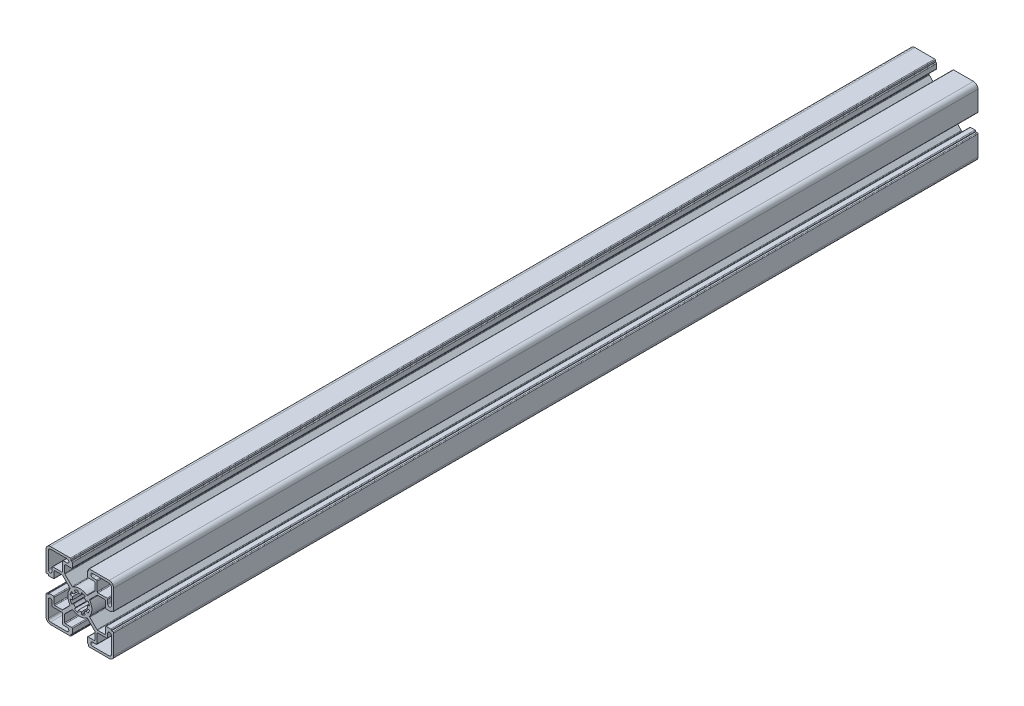
SolidWorks part; units mm, degrees
material "6063-O"
ref_plane "Front Plane" through (0, 0, 0) normal (0, 0, 1) x (1, 0, 0)
ref_plane "Top Plane" through (0, 0, 0) normal (0, 1, 0) x (1, 0, 0)
ref_plane "Right Plane" through (0, 0, 0) normal (1, 0, 0) x (0, 0, -1)
sketch "Sketch1" plane through (0, 0, 0) normal (0, 0, 1) x (1, 0, 0)
  line L0 (0, 22.5) -> (0, -22.5) construction
  line L1 (22.5, 0) -> (-22.5, 0) construction
  line L2 (-5.8, 22.5) -> (5.8, 22.5) construction
  line L3 (-5, 21) -> (5, 21) construction
  line L4 (-10.05, 10.05) -> (10.05, 10.05) construction
  line L5 (0, 0) -> (-10.05, 10.05) construction
  circle A0 centre (0, 0) radius 5 construction
  point P4 (0, 0)
  point P8 (0, 0)
  point P10 (0, 8)
  point P14 (0, 22.5)
  point P17 (0, 21)
  point P19 (0, 10.05)
sketch "Sketch2" plane through (0, 0, 0) normal (1, 0, 0) x (0, 0, -1)
  line L0 (152.4, 0) -> (-152.4, 0) construction
  point P4 (0, 0)
  dimension "D1" = 304.8
sketch "Sketch3" plane through (0, 0, 0) normal (0, 0, 1) x (1, 0, 0)
  line L5 (-21, 8.5375) -> (-21, 19.5)
  line L9 (0, 0) -> (-22.5, 22.5) construction
  line L10 (-11.55, -10.05) -> (-6.3569, -4.8569)
  line L11 (-19.5, 21) -> (-8.5375, 21)
  line L38 (-5.8, 22.5) -> (-5.8, 21)
  line L46 (-5.8, 21) -> (-5, 21)
  line L62 (-5, 21) -> (-5, 17.025)
  line L74 (-5, 17.025) -> (-10.05, 17.025)
  line L76 (-10.05, 17.025) -> (-10.05, 11.55)
  line L77 (-10.05, 11.55) -> (-4.8569, 6.3569)
  line L78 (-18.525, 8.5375) -> (-18.525, 11.55)
  line L79 (-10.05, 17.025) -> (-10.05, 22.5) construction
  line L80 (0, 22.5) -> (0, -22.5) construction
  line L81 (-5.8, 22.5) -> (5.8, 22.5) construction
  line L82 (10.05, 11.55) -> (4.8569, 6.3569)
  line L83 (10.05, 17.025) -> (10.05, 11.55)
  line L84 (5, 17.025) -> (10.05, 17.025)
  line L85 (5, 21) -> (5, 17.025)
  line L86 (5.8, 21) -> (5, 21)
  line L87 (5.8, 22.5) -> (5.8, 21)
  line L88 (-22.5, -5.8) -> (-21, -5.8)
  line L89 (-21, -5.8) -> (-21, -5)
  line L90 (-21, -5) -> (-17.025, -5)
  line L91 (-17.025, -5) -> (-17.025, -10.05)
  line L92 (-17.025, -10.05) -> (-11.55, -10.05)
  line L93 (-11.55, -10.05) -> (-6.3569, -4.8569)
  line L94 (-11.55, 10.05) -> (-6.3569, 4.8569)
  line L95 (-17.025, 10.05) -> (-11.55, 10.05)
  line L96 (-17.025, 5) -> (-17.025, 10.05)
  line L97 (-21, 5) -> (-17.025, 5)
  line L98 (-21, 5.8) -> (-21, 5)
  line L99 (-22.5, 5.8) -> (-21, 5.8)
  line L100 (-22.5, 5.8) -> (-22.5, 19.5)
  line L101 (-19.5, 22.5) -> (-5.8, 22.5)
  line L102 (-18.525, 11.55) -> (-11.55, 11.55)
  line L103 (-8.5375, 18.525) -> (-11.55, 18.525)
  line L104 (-11.55, 18.525) -> (-11.55, 11.55)
  line L108 (5.8, -22.5) -> (5.8, -21)
  line L113 (5.8, -21) -> (5, -21)
  line L117 (5.8, 22.5) -> (19.5, 22.5)
  line L118 (22.5, 19.5) -> (22.5, 5.8)
  line L119 (19.5, -22.5) -> (5.8, -22.5)
  line L120 (0, 0) -> (22.5, 0) construction
  line L121 (-22.5, -19.5) -> (-22.5, -5.8)
  line L136 (5, -21) -> (5, -17.025)
  line L137 (5, -17.025) -> (10.05, -17.025)
  line L138 (10.05, -17.025) -> (10.05, -11.55)
  line L139 (10.05, -11.55) -> (4.8569, -6.3569)
  line L140 (-10.05, -11.55) -> (-4.8569, -6.3569)
  line L141 (-10.05, -17.025) -> (-10.05, -11.55)
  line L142 (-5, -17.025) -> (-10.05, -17.025)
  line L143 (-5, -21) -> (-5, -17.025)
  line L144 (-5.8, -21) -> (-5, -21)
  line L145 (-5.8, -22.5) -> (-5.8, -21)
  line L146 (-5.8, -22.5) -> (-19.5, -22.5)
  line L147 (22.5, 5.8) -> (21, 5.8)
  line L148 (21, 5.8) -> (21, 5)
  line L149 (21, 5) -> (17.025, 5)
  line L150 (17.025, 5) -> (17.025, 10.05)
  line L151 (17.025, 10.05) -> (11.55, 10.05)
  line L152 (11.55, 10.05) -> (6.3569, 4.8569)
  line L153 (11.55, -10.05) -> (6.3569, -4.8569)
  line L154 (17.025, -10.05) -> (11.55, -10.05)
  line L155 (17.025, -5) -> (17.025, -10.05)
  line L156 (21, -5) -> (17.025, -5)
  line L157 (21, -5.8) -> (21, -5)
  line L158 (22.5, -5.8) -> (21, -5.8)
  line L159 (11.55, -10.05) -> (6.3569, -4.8569)
  line L160 (22.5, -5.8) -> (22.5, -19.5)
  line L161 (8.5375, 21) -> (19.5, 21)
  line L162 (21, 19.5) -> (21, 8.5375)
  line L163 (8.5375, 18.525) -> (11.55, 18.525)
  line L164 (11.55, 18.525) -> (11.55, 11.55)
  line L165 (18.525, 8.5375) -> (18.525, 11.55)
  line L166 (18.525, 11.55) -> (11.55, 11.55)
  line L167 (21, -8.5375) -> (21, -19.5)
  line L168 (19.5, -21) -> (8.5375, -21)
  line L169 (18.525, -8.5375) -> (18.525, -11.55)
  line L170 (18.525, -11.55) -> (11.55, -11.55)
  line L171 (8.5375, -18.525) -> (11.55, -18.525)
  line L172 (11.55, -18.525) -> (11.55, -11.55)
  line L173 (-8.5375, -21) -> (-19.5, -21)
  line L174 (-21, -19.5) -> (-21, -8.5375)
  line L175 (-8.5375, -18.525) -> (-11.55, -18.525)
  line L176 (-11.55, -18.525) -> (-11.55, -11.55)
  line L177 (-18.525, -8.5375) -> (-18.525, -11.55)
  line L178 (-18.525, -11.55) -> (-11.55, -11.55)
  line L179 (0, 0) -> (-11.55, 11.55) construction
  line L180 (0, 0) -> (11.55, 11.55) construction
  arc A2 (-21, 19.5) -> (-19.5, 21) centre (-19.5, 19.5) cw
  arc A73 (-4.8569, 6.3569) -> (4.8569, 6.3569) centre (0, 0) cw
  arc A74 (-6.3569, 4.8569) -> (-6.3569, -4.8569) centre (0, 0) ccw
  arc A75 (-19.5, 22.5) -> (-22.5, 19.5) centre (-19.5, 19.5) ccw
  arc A76 (-21, 8.5375) -> (-18.525, 8.5375) centre (-19.7625, 8.5375) ccw
  arc A77 (-8.5375, 21) -> (-8.5375, 18.525) centre (-8.5375, 19.7625) cw
  arc A80 (19.5, 22.5) -> (22.5, 19.5) centre (19.5, 19.5) cw
  arc A81 (22.5, -19.5) -> (19.5, -22.5) centre (19.5, -19.5) cw
  arc A82 (-19.5, -22.5) -> (-22.5, -19.5) centre (-19.5, -19.5) cw
  circle A88 centre (0, 0) radius 5 construction
  circle A89 centre (0, 0) radius 5
  arc A90 (-4.8569, -6.3569) -> (4.8569, -6.3569) centre (0, 0) ccw
  arc A91 (19.5, 21) -> (21, 19.5) centre (19.5, 19.5) cw
  arc A92 (6.3569, 4.8569) -> (6.3569, -4.8569) centre (0, 0) cw
  arc A93 (8.5375, 21) -> (8.5375, 18.525) centre (8.5375, 19.7625) ccw
  arc A94 (21, 8.5375) -> (18.525, 8.5375) centre (19.7625, 8.5375) cw
  arc A95 (21, -19.5) -> (19.5, -21) centre (19.5, -19.5) cw
  arc A96 (21, -8.5375) -> (18.525, -8.5375) centre (19.7625, -8.5375) ccw
  arc A97 (8.5375, -21) -> (8.5375, -18.525) centre (8.5375, -19.7625) cw
  arc A98 (-19.5, -21) -> (-21, -19.5) centre (-19.5, -19.5) cw
  arc A99 (-8.5375, -21) -> (-8.5375, -18.525) centre (-8.5375, -19.7625) ccw
  arc A100 (-21, -8.5375) -> (-18.525, -8.5375) centre (-19.7625, -8.5375) cw
  point P54 (-14.2875, 10.05)
  dimension "D2" = 3
  dimension "D3" = 1.5
  dimension "D4" = 1.5
  dimension "D5" = 1.5
  dimension "D6" = 90
  dimension "D1" = 4
extrude "Boss-Extrude1" add sketch "Sketch3" along normal up to vertex (152.4 mm away) and the other way up to vertex (152.4 mm away) contours A92 L152 L151 L150 L149 L148 L147 L118 A80 L117 L87 L86 L85 L84 L83 L82 A73 L77 L76 L74 L62 L46 L38 L101 A75 L100 L99 L98 L97 L96 L95 L94 A74 L10 L92 L91 L90 L89 L88 L121 A82 L146 L145 L144 L143 L142 L141 L140 A90 L139 L138 up to point (0, 0, 152.4) other way up to point (0, 0, -152.4)
fillet "Fillet1" radius 0.5 58 edges at (5, 21, 0) (5.8, 22.5, 0) (-5.8, 22.5, 0) (-5, 21, 0) (-10.05, 17.025, 0) (-5, 17.025, 0) (5, 17.025, 0) (-22.5, -5.8, 0) (-21, -5, 0) (-17.025, -5, 0) (-17.025, -10.05, 0) (-11.55, -10.05, 0) (-6.3569, -4.8569, 0) (-6.3569, 4.8569, 0) (-11.55, 10.05, 0) (-17.025, 10.05, 0) (-17.025, 5, 0) (-22.5, 5.8, 0) (-21, 5, 0) (-18.525, 11.55, 0) (-11.55, 11.55, 0) (-11.55, 18.525, 0) (4.8569, 6.3569, 0) (-4.8569, 6.3569, 0) (-10.05, 11.55, 0) (10.05, 17.025, 0) (10.05, 11.55, 0) (22.5, -5.8, 0) (21, -5, 0) (17.025, -5, 0) (17.025, -10.05, 0) (6.3569, 4.8569, 0) (11.55, 10.05, 0) (22.5, 5.8, 0) (21, 5, 0) (17.025, 5, 0) (4.8569, -6.3569, 0) (11.55, -11.55, 0) (-11.55, -11.55, 0) (18.525, -11.55, 0) (11.55, -18.525, 0) (10.05, -17.025, 0) (5, -17.025, 0) (5, -21, 0) (5.8, -22.5, 0) (-5.8, -22.5, 0) (-5, -21, 0) (-5, -17.025, 0) (-10.05, -17.025, 0) (-11.55, -18.525, 0) (11.55, 18.525, 0) (18.525, 11.55, 0) (11.55, 11.55, 0) (11.55, -10.05, 0) (6.3569, -4.8569, 0) (-4.8569, -6.3569, 0) (10.05, -11.55, 0) (-10.05, -11.55, 0)
sketch "Sketch4" plane through (0, 0, 152.4) normal (0, 0, 1) x (1, 0, 0)
  line L0 (-1.2681, 6.3751) -> (-0.9755, 4.9039)
  line L1 (0, 0) -> (0, 8) construction
  line L2 (-3.6112, 5.4046) -> (-2.7779, 4.1573)
  line L3 (1.2681, 6.3751) -> (0.9755, 4.9039)
  line L4 (3.6112, 5.4046) -> (2.7779, 4.1573)
  line L5 (5.4046, 3.6112) -> (4.1573, 2.7779)
  line L6 (6.3751, 1.2681) -> (4.9039, 0.9755)
  line L7 (6.3751, -1.2681) -> (4.9039, -0.9755)
  line L8 (5.4046, -3.6112) -> (4.1573, -2.7779)
  line L9 (3.6112, -5.4046) -> (2.7779, -4.1573)
  line L10 (1.2681, -6.3751) -> (0.9755, -4.9039)
  line L11 (-1.2681, -6.3751) -> (-0.9755, -4.9039)
  line L12 (-3.6112, -5.4046) -> (-2.7779, -4.1573)
  line L13 (-5.4046, -3.6112) -> (-4.1573, -2.7779)
  line L14 (-6.3751, -1.2681) -> (-4.9039, -0.9755)
  line L15 (-6.3751, 1.2681) -> (-4.9039, 0.9755)
  line L16 (-5.4046, 3.6112) -> (-4.1573, 2.7779)
  line L17 (0, 0) -> (-0.9755, 4.9039) construction
  line L18 (0, 0) -> (2.7779, 4.1573) construction
  arc A0 (-1.2681, 6.3751) -> (-3.6112, 5.4046) centre (0, 0) ccw
  circle A1 centre (0, 0) radius 5 construction
  arc A2 (-0.9755, 4.9039) -> (-2.7779, 4.1573) centre (0, 0) ccw
  arc A4 (2.7779, 4.1573) -> (0.9755, 4.9039) centre (0, 0) ccw
  arc A5 (3.6112, 5.4046) -> (1.2681, 6.3751) centre (0, 0) ccw
  arc A6 (4.9039, 0.9755) -> (4.1573, 2.7779) centre (0, 0) ccw
  arc A7 (6.3751, 1.2681) -> (5.4046, 3.6112) centre (0, 0) ccw
  arc A8 (4.1573, -2.7779) -> (4.9039, -0.9755) centre (0, 0) ccw
  arc A9 (5.4046, -3.6112) -> (6.3751, -1.2681) centre (0, 0) ccw
  arc A10 (0.9755, -4.9039) -> (2.7779, -4.1573) centre (0, 0) ccw
  arc A11 (1.2681, -6.3751) -> (3.6112, -5.4046) centre (0, 0) ccw
  arc A12 (-2.7779, -4.1573) -> (-0.9755, -4.9039) centre (0, 0) ccw
  arc A13 (-3.6112, -5.4046) -> (-1.2681, -6.3751) centre (0, 0) ccw
  arc A14 (-4.9039, -0.9755) -> (-4.1573, -2.7779) centre (0, 0) ccw
  arc A15 (-6.3751, -1.2681) -> (-5.4046, -3.6112) centre (0, 0) ccw
  arc A16 (-4.1573, 2.7779) -> (-4.9039, 0.9755) centre (0, 0) ccw
  arc A17 (-5.4046, 3.6112) -> (-6.3751, 1.2681) centre (0, 0) ccw
  dimension "D1" = 1.5
  dimension "D2" = 22.5
  dimension "D5" = 45
  dimension "D4" = 8
extrude "Cut-Extrude1" cut sketch "Sketch4" against normal through all
sketch "Sketch5" plane through (0, 0, 152.4) normal (0, 0, 1) x (1, 0, 0)
  line L6 (-11.55, -18.025) -> (-11.55, -12.05)
  line L7 (-8.5375, -18.525) -> (-11.05, -18.525)
  line L8 (-19.5, -21) -> (-8.5375, -21)
  line L9 (-21, -8.5375) -> (-21, -19.5)
  line L10 (-18.525, -11.55) -> (-18.525, -8.5375)
  line L11 (-12.05, -11.55) -> (-18.525, -11.55)
  line L12 (-11.55, -18.025) -> (-11.55, -12.05)
  line L13 (-8.5375, -18.525) -> (-11.05, -18.525)
  line L14 (-19.5, -21) -> (-8.5375, -21)
  line L15 (-21, -8.5375) -> (-21, -19.5)
  line L16 (-0.9755, 4.9039) -> (-1.2681, 6.3751)
  line L17 (1.2681, 6.3751) -> (0.9755, 4.9039)
  line L18 (2.7779, 4.1573) -> (3.6112, 5.4046)
  line L19 (5.4046, 3.6112) -> (4.1573, 2.7779)
  line L20 (4.9039, 0.9755) -> (6.3751, 1.2681)
  line L21 (6.3751, -1.2681) -> (4.9039, -0.9755)
  line L22 (4.1573, -2.7779) -> (5.4046, -3.6112)
  line L23 (3.6112, -5.4046) -> (2.7779, -4.1573)
  line L24 (0.9755, -4.9039) -> (1.2681, -6.3751)
  line L25 (-1.2681, -6.3751) -> (-0.9755, -4.9039)
  line L26 (-2.7779, -4.1573) -> (-3.6112, -5.4046)
  line L27 (-5.4046, -3.6112) -> (-4.1573, -2.7779)
  line L28 (-4.9039, -0.9755) -> (-6.3751, -1.2681)
  line L29 (-6.3751, 1.2681) -> (-4.9039, 0.9755)
  line L30 (-4.1573, 2.7779) -> (-5.4046, 3.6112)
  line L31 (-3.6112, 5.4046) -> (-2.7779, 4.1573)
  line L32 (-0.9755, 4.9039) -> (-1.2681, 6.3751)
  line L33 (1.2681, 6.3751) -> (0.9755, 4.9039)
  line L34 (2.7779, 4.1573) -> (3.6112, 5.4046)
  line L35 (5.4046, 3.6112) -> (4.1573, 2.7779)
  line L36 (4.9039, 0.9755) -> (6.3751, 1.2681)
  line L37 (6.3751, -1.2681) -> (4.9039, -0.9755)
  line L38 (4.1573, -2.7779) -> (5.4046, -3.6112)
  line L39 (3.6112, -5.4046) -> (2.7779, -4.1573)
  line L40 (0.9755, -4.9039) -> (1.2681, -6.3751)
  line L41 (-1.2681, -6.3751) -> (-0.9755, -4.9039)
  line L42 (-2.7779, -4.1573) -> (-3.6112, -5.4046)
  line L43 (-5.4046, -3.6112) -> (-4.1573, -2.7779)
  line L44 (-4.9039, -0.9755) -> (-6.3751, -1.2681)
  line L45 (-6.3751, 1.2681) -> (-4.9039, 0.9755)
  line L46 (-4.1573, 2.7779) -> (-5.4046, 3.6112)
  line L47 (-3.6112, 5.4046) -> (-2.7779, 4.1573)
  line L48 (-18.525, -11.55) -> (-18.525, -8.5375)
  line L49 (-12.05, -11.55) -> (-18.525, -11.55)
  line L50 (18.025, -11.55) -> (12.05, -11.55)
  line L51 (18.525, -8.5375) -> (18.525, -11.05)
  line L52 (21, -19.5) -> (21, -8.5375)
  line L53 (8.5375, -21) -> (19.5, -21)
  line L54 (11.05, -18.525) -> (8.5375, -18.525)
  line L55 (11.55, -12.05) -> (11.55, -18.025)
  line L56 (22.5, -19.5) -> (22.5, -6.3)
  line L57 (22, -5.8) -> (21, -5.8)
  line L58 (21, -5.8) -> (21, -5.5)
  line L59 (20.5, -5) -> (17.525, -5)
  line L60 (17.025, -5.5) -> (17.025, -9.55)
  line L61 (16.525, -10.05) -> (11.7571, -10.05)
  line L62 (11.4036, -9.9036) -> (6.6582, -5.1582)
  line L63 (6.6582, 5.1582) -> (11.4036, 9.9036)
  line L64 (11.7571, 10.05) -> (17.025, 10.05)
  line L65 (17.025, 10.05) -> (17.025, 5.5)
  line L66 (17.525, 5) -> (20.5, 5)
  line L67 (21, 5.5) -> (21, 5.8)
  line L68 (21, 5.8) -> (22, 5.8)
  line L69 (22.5, 6.3) -> (22.5, 19.5)
  line L70 (19.5, 22.5) -> (6.3, 22.5)
  line L71 (5.8, 22) -> (5.8, 21)
  line L72 (5.8, 21) -> (5.5, 21)
  line L73 (5, 20.5) -> (5, 17.525)
  line L74 (5.5, 17.025) -> (9.55, 17.025)
  line L75 (10.05, 16.525) -> (10.05, 11.7571)
  line L76 (9.9036, 11.4036) -> (5.1582, 6.6582)
  line L77 (-5.1582, 6.6582) -> (-9.9036, 11.4036)
  line L78 (-10.05, 11.7571) -> (-10.05, 16.525)
  line L79 (-9.55, 17.025) -> (-5.5, 17.025)
  line L80 (-5, 17.525) -> (-5, 20.5)
  line L81 (-5.5, 21) -> (-5.8, 21)
  line L82 (-5.8, 21) -> (-5.8, 22)
  line L83 (-6.3, 22.5) -> (-19.5, 22.5)
  line L84 (-22.5, 19.5) -> (-22.5, 6.3)
  line L85 (-22, 5.8) -> (-21, 5.8)
  line L86 (-21, 5.8) -> (-21, 5.5)
  line L87 (-20.5, 5) -> (-17.525, 5)
  line L88 (-17.025, 5.5) -> (-17.025, 9.55)
  line L89 (-16.525, 10.05) -> (-11.7571, 10.05)
  line L90 (-11.4036, 9.9036) -> (-6.6582, 5.1582)
  line L91 (-6.6582, -5.1582) -> (-11.4036, -9.9036)
  line L92 (-11.7571, -10.05) -> (-16.525, -10.05)
  line L93 (-17.025, -9.55) -> (-17.025, -5.5)
  line L94 (-17.525, -5) -> (-20.5, -5)
  line L95 (-21, -5.5) -> (-21, -5.8)
  line L96 (-21, -5.8) -> (-22, -5.8)
  line L97 (-22.5, -6.3) -> (-22.5, -19.5)
  line L98 (-19.5, -22.5) -> (-6.3, -22.5)
  line L99 (-5.8, -22) -> (-5.8, -21)
  line L100 (-5.8, -21) -> (-5.5, -21)
  line L101 (-5, -20.5) -> (-5, -17.525)
  line L102 (-5.5, -17.025) -> (-9.55, -17.025)
  line L103 (-10.05, -16.525) -> (-10.05, -11.7571)
  line L104 (-9.9036, -11.4036) -> (-5.1582, -6.6582)
  line L105 (5.1582, -6.6582) -> (9.9036, -11.4036)
  line L106 (10.05, -11.7571) -> (10.05, -16.525)
  line L107 (9.55, -17.025) -> (5.5, -17.025)
  line L108 (5, -17.525) -> (5, -20.5)
  line L109 (5.5, -21) -> (5.8, -21)
  line L110 (5.8, -21) -> (5.8, -22)
  line L111 (6.3, -22.5) -> (19.5, -22.5)
  line L112 (22.5, -19.5) -> (22.5, -6.3)
  line L113 (22, -5.8) -> (21, -5.8)
  line L114 (21, -5.8) -> (21, -5.5)
  line L115 (20.5, -5) -> (17.525, -5)
  line L116 (17.025, -5.5) -> (17.025, -9.55)
  line L117 (16.525, -10.05) -> (11.7571, -10.05)
  line L118 (11.4036, -9.9036) -> (6.6582, -5.1582)
  line L119 (6.6582, 5.1582) -> (11.4036, 9.9036)
  line L120 (11.7571, 10.05) -> (17.025, 10.05)
  line L121 (17.025, 10.05) -> (17.025, 5.5)
  line L122 (17.525, 5) -> (20.5, 5)
  line L123 (21, 5.5) -> (21, 5.8)
  line L124 (21, 5.8) -> (22, 5.8)
  line L125 (22.5, 6.3) -> (22.5, 19.5)
  line L126 (19.5, 22.5) -> (6.3, 22.5)
  line L127 (5.8, 22) -> (5.8, 21)
  line L128 (5.8, 21) -> (5.5, 21)
  line L129 (5, 20.5) -> (5, 17.525)
  line L130 (5.5, 17.025) -> (9.55, 17.025)
  line L131 (10.05, 16.525) -> (10.05, 11.7571)
  line L132 (9.9036, 11.4036) -> (5.1582, 6.6582)
  line L133 (-5.1582, 6.6582) -> (-9.9036, 11.4036)
  line L134 (-10.05, 11.7571) -> (-10.05, 16.525)
  line L135 (-9.55, 17.025) -> (-5.5, 17.025)
  line L136 (-5, 17.525) -> (-5, 20.5)
  line L137 (-5.5, 21) -> (-5.8, 21)
  line L138 (-5.8, 21) -> (-5.8, 22)
  line L139 (-6.3, 22.5) -> (-19.5, 22.5)
  line L140 (-22.5, 19.5) -> (-22.5, 6.3)
  line L141 (-22, 5.8) -> (-21, 5.8)
  line L142 (-21, 5.8) -> (-21, 5.5)
  line L143 (-20.5, 5) -> (-17.525, 5)
  line L144 (-17.025, 5.5) -> (-17.025, 9.55)
  line L145 (-16.525, 10.05) -> (-11.7571, 10.05)
  line L146 (-11.4036, 9.9036) -> (-6.6582, 5.1582)
  line L147 (-6.6582, -5.1582) -> (-11.4036, -9.9036)
  line L148 (-11.7571, -10.05) -> (-16.525, -10.05)
  line L149 (-17.025, -9.55) -> (-17.025, -5.5)
  line L150 (-17.525, -5) -> (-20.5, -5)
  line L151 (-21, -5.5) -> (-21, -5.8)
  line L152 (-21, -5.8) -> (-22, -5.8)
  line L153 (-22.5, -6.3) -> (-22.5, -19.5)
  line L154 (-19.5, -22.5) -> (-6.3, -22.5)
  line L155 (-5.8, -22) -> (-5.8, -21)
  line L156 (-5.8, -21) -> (-5.5, -21)
  line L157 (-5, -20.5) -> (-5, -17.525)
  line L158 (-5.5, -17.025) -> (-9.55, -17.025)
  line L159 (-10.05, -16.525) -> (-10.05, -11.7571)
  line L160 (-9.9036, -11.4036) -> (-5.1582, -6.6582)
  line L161 (5.1582, -6.6582) -> (9.9036, -11.4036)
  line L162 (10.05, -11.7571) -> (10.05, -16.525)
  line L163 (9.55, -17.025) -> (5.5, -17.025)
  line L164 (5, -17.525) -> (5, -20.5)
  line L165 (5.5, -21) -> (5.8, -21)
  line L166 (5.8, -21) -> (5.8, -22)
  line L167 (6.3, -22.5) -> (19.5, -22.5)
  line L168 (18.025, -11.55) -> (12.05, -11.55)
  line L169 (18.525, -8.5375) -> (18.525, -11.05)
  line L170 (21, -19.5) -> (21, -8.5375)
  line L171 (8.5375, -21) -> (19.5, -21)
  line L172 (11.05, -18.525) -> (8.5375, -18.525)
  line L173 (11.55, -12.05) -> (11.55, -18.025)
  line L174 (11.55, 18.025) -> (11.55, 12.05)
  line L175 (8.5375, 18.525) -> (11.05, 18.525)
  line L176 (19.5, 21) -> (8.5375, 21)
  line L177 (21, 8.5375) -> (21, 19.5)
  line L178 (18.525, 11.05) -> (18.525, 8.5375)
  line L179 (12.05, 11.55) -> (18.025, 11.55)
  line L180 (11.55, 18.025) -> (11.55, 12.05)
  line L181 (8.5375, 18.525) -> (11.05, 18.525)
  line L182 (19.5, 21) -> (8.5375, 21)
  line L183 (21, 8.5375) -> (21, 19.5)
  line L184 (18.525, 11.05) -> (18.525, 8.5375)
  line L185 (12.05, 11.55) -> (18.025, 11.55)
  line L186 (-18.025, 11.55) -> (-12.05, 11.55)
  line L187 (-18.525, 8.5375) -> (-18.525, 11.05)
  line L188 (-21, 19.5) -> (-21, 8.5375)
  line L189 (-8.5375, 21) -> (-19.5, 21)
  line L190 (-11.05, 18.525) -> (-8.5375, 18.525)
  line L191 (-11.55, 12.05) -> (-11.55, 18.025)
  line L192 (-18.025, 11.55) -> (-12.05, 11.55)
  line L193 (-18.525, 8.5375) -> (-18.525, 11.05)
  line L194 (-21, 19.5) -> (-21, 8.5375)
  line L195 (-8.5375, 21) -> (-19.5, 21)
  line L196 (-11.05, 18.525) -> (-8.5375, 18.525)
  line L197 (-11.55, 12.05) -> (-11.55, 18.025)
  arc A5 (-11.55, -18.025) -> (-11.05, -18.525) centre (-11.05, -18.025) ccw
  arc A6 (-8.5375, -21) -> (-8.5375, -18.525) centre (-8.5375, -19.7625) ccw
  arc A7 (-21, -19.5) -> (-19.5, -21) centre (-19.5, -19.5) ccw
  arc A8 (-18.525, -8.5375) -> (-21, -8.5375) centre (-19.7625, -8.5375) ccw
  arc A9 (-11.55, -12.05) -> (-12.05, -11.55) centre (-12.05, -12.05) ccw
  arc A10 (-11.55, -18.025) -> (-11.05, -18.525) centre (-11.05, -18.025) ccw
  arc A11 (-8.5375, -21) -> (-8.5375, -18.525) centre (-8.5375, -19.7625) ccw
  arc A12 (-21, -19.5) -> (-19.5, -21) centre (-19.5, -19.5) ccw
  arc A13 (-18.525, -8.5375) -> (-21, -8.5375) centre (-19.7625, -8.5375) ccw
  arc A14 (-11.55, -12.05) -> (-12.05, -11.55) centre (-12.05, -12.05) ccw
  arc A16 (0.9755, 4.9039) -> (-0.9755, 4.9039) centre (0, 0) ccw
  arc A17 (3.6112, 5.4046) -> (1.2681, 6.3751) centre (0, 0) ccw
  arc A18 (4.1573, 2.7779) -> (2.7779, 4.1573) centre (0, 0) ccw
  arc A19 (6.3751, 1.2681) -> (5.4046, 3.6112) centre (0, 0) ccw
  arc A20 (4.9039, -0.9755) -> (4.9039, 0.9755) centre (0, 0) ccw
  arc A21 (5.4046, -3.6112) -> (6.3751, -1.2681) centre (0, 0) ccw
  arc A22 (2.7779, -4.1573) -> (4.1573, -2.7779) centre (0, 0) ccw
  arc A23 (1.2681, -6.3751) -> (3.6112, -5.4046) centre (0, 0) ccw
  arc A24 (-0.9755, -4.9039) -> (0.9755, -4.9039) centre (0, 0) ccw
  arc A25 (-3.6112, -5.4046) -> (-1.2681, -6.3751) centre (0, 0) ccw
  arc A26 (-4.1573, -2.7779) -> (-2.7779, -4.1573) centre (0, 0) ccw
  arc A27 (-6.3751, -1.2681) -> (-5.4046, -3.6112) centre (0, 0) ccw
  arc A28 (-4.9039, 0.9755) -> (-4.9039, -0.9755) centre (0, 0) ccw
  arc A29 (-5.4046, 3.6112) -> (-6.3751, 1.2681) centre (0, 0) ccw
  arc A30 (-2.7779, 4.1573) -> (-4.1573, 2.7779) centre (0, 0) ccw
  arc A31 (-1.2681, 6.3751) -> (-3.6112, 5.4046) centre (0, 0) ccw
  arc A32 (0.9755, 4.9039) -> (-0.9755, 4.9039) centre (0, 0) ccw
  arc A33 (3.6112, 5.4046) -> (1.2681, 6.3751) centre (0, 0) ccw
  arc A34 (4.1573, 2.7779) -> (2.7779, 4.1573) centre (0, 0) ccw
  arc A35 (6.3751, 1.2681) -> (5.4046, 3.6112) centre (0, 0) ccw
  arc A36 (4.9039, -0.9755) -> (4.9039, 0.9755) centre (0, 0) ccw
  arc A37 (5.4046, -3.6112) -> (6.3751, -1.2681) centre (0, 0) ccw
  arc A38 (2.7779, -4.1573) -> (4.1573, -2.7779) centre (0, 0) ccw
  arc A39 (1.2681, -6.3751) -> (3.6112, -5.4046) centre (0, 0) ccw
  arc A40 (-0.9755, -4.9039) -> (0.9755, -4.9039) centre (0, 0) ccw
  arc A41 (-3.6112, -5.4046) -> (-1.2681, -6.3751) centre (0, 0) ccw
  arc A42 (-4.1573, -2.7779) -> (-2.7779, -4.1573) centre (0, 0) ccw
  arc A43 (-6.3751, -1.2681) -> (-5.4046, -3.6112) centre (0, 0) ccw
  arc A44 (-4.9039, 0.9755) -> (-4.9039, -0.9755) centre (0, 0) ccw
  arc A45 (-5.4046, 3.6112) -> (-6.3751, 1.2681) centre (0, 0) ccw
  arc A46 (-2.7779, 4.1573) -> (-4.1573, 2.7779) centre (0, 0) ccw
  arc A47 (-1.2681, 6.3751) -> (-3.6112, 5.4046) centre (0, 0) ccw
  arc A48 (18.025, -11.55) -> (18.525, -11.05) centre (18.025, -11.05) ccw
  arc A49 (21, -8.5375) -> (18.525, -8.5375) centre (19.7625, -8.5375) ccw
  arc A50 (19.5, -21) -> (21, -19.5) centre (19.5, -19.5) ccw
  arc A51 (8.5375, -18.525) -> (8.5375, -21) centre (8.5375, -19.7625) ccw
  arc A52 (11.05, -18.525) -> (11.55, -18.025) centre (11.05, -18.025) ccw
  arc A53 (12.05, -11.55) -> (11.55, -12.05) centre (12.05, -12.05) ccw
  arc A54 (18.025, -11.55) -> (18.525, -11.05) centre (18.025, -11.05) ccw
  arc A55 (22.5, -6.3) -> (22, -5.8) centre (22, -6.3) ccw
  arc A56 (21, -5.5) -> (20.5, -5) centre (20.5, -5.5) ccw
  arc A57 (17.525, -5) -> (17.025, -5.5) centre (17.525, -5.5) ccw
  arc A58 (16.525, -10.05) -> (17.025, -9.55) centre (16.525, -9.55) ccw
  arc A59 (11.4036, -9.9036) -> (11.7571, -10.05) centre (11.7571, -9.55) ccw
  arc A60 (6.5993, -4.522) -> (6.6582, -5.1582) centre (7.0118, -4.8047) ccw
  arc A61 (6.5993, -4.522) -> (6.5993, 4.522) centre (0, 0) ccw
  arc A62 (6.6582, 5.1582) -> (6.5993, 4.522) centre (7.0118, 4.8047) ccw
  arc A63 (11.7571, 10.05) -> (11.4036, 9.9036) centre (11.7571, 9.55) ccw
  arc A64 (17.025, 5.5) -> (17.525, 5) centre (17.525, 5.5) ccw
  arc A65 (20.5, 5) -> (21, 5.5) centre (20.5, 5.5) ccw
  arc A66 (22, 5.8) -> (22.5, 6.3) centre (22, 6.3) ccw
  arc A67 (22.5, 19.5) -> (19.5, 22.5) centre (19.5, 19.5) ccw
  arc A68 (6.3, 22.5) -> (5.8, 22) centre (6.3, 22) ccw
  arc A69 (5.5, 21) -> (5, 20.5) centre (5.5, 20.5) ccw
  arc A70 (5, 17.525) -> (5.5, 17.025) centre (5.5, 17.525) ccw
  arc A71 (10.05, 16.525) -> (9.55, 17.025) centre (9.55, 16.525) ccw
  arc A72 (9.9036, 11.4036) -> (10.05, 11.7571) centre (9.55, 11.7571) ccw
  arc A73 (4.522, 6.5993) -> (5.1582, 6.6582) centre (4.8047, 7.0118) ccw
  arc A74 (4.522, 6.5993) -> (-4.522, 6.5993) centre (0, 0) ccw
  arc A75 (-5.1582, 6.6582) -> (-4.522, 6.5993) centre (-4.8047, 7.0118) ccw
  arc A76 (-10.05, 11.7571) -> (-9.9036, 11.4036) centre (-9.55, 11.7571) ccw
  arc A77 (-9.55, 17.025) -> (-10.05, 16.525) centre (-9.55, 16.525) ccw
  arc A78 (-5.5, 17.025) -> (-5, 17.525) centre (-5.5, 17.525) ccw
  arc A79 (-5, 20.5) -> (-5.5, 21) centre (-5.5, 20.5) ccw
  arc A80 (-5.8, 22) -> (-6.3, 22.5) centre (-6.3, 22) ccw
  arc A81 (-19.5, 22.5) -> (-22.5, 19.5) centre (-19.5, 19.5) ccw
  arc A82 (-22.5, 6.3) -> (-22, 5.8) centre (-22, 6.3) ccw
  arc A83 (-21, 5.5) -> (-20.5, 5) centre (-20.5, 5.5) ccw
  arc A84 (-17.525, 5) -> (-17.025, 5.5) centre (-17.525, 5.5) ccw
  arc A85 (-16.525, 10.05) -> (-17.025, 9.55) centre (-16.525, 9.55) ccw
  arc A86 (-11.4036, 9.9036) -> (-11.7571, 10.05) centre (-11.7571, 9.55) ccw
  arc A87 (-6.5993, 4.522) -> (-6.6582, 5.1582) centre (-7.0118, 4.8047) ccw
  arc A88 (-6.5993, 4.522) -> (-6.5993, -4.522) centre (0, 0) ccw
  arc A89 (-6.6582, -5.1582) -> (-6.5993, -4.522) centre (-7.0118, -4.8047) ccw
  arc A90 (-11.7571, -10.05) -> (-11.4036, -9.9036) centre (-11.7571, -9.55) ccw
  arc A91 (-17.025, -9.55) -> (-16.525, -10.05) centre (-16.525, -9.55) ccw
  arc A92 (-17.025, -5.5) -> (-17.525, -5) centre (-17.525, -5.5) ccw
  arc A93 (-20.5, -5) -> (-21, -5.5) centre (-20.5, -5.5) ccw
  arc A94 (-22, -5.8) -> (-22.5, -6.3) centre (-22, -6.3) ccw
  arc A95 (-22.5, -19.5) -> (-19.5, -22.5) centre (-19.5, -19.5) ccw
  arc A96 (-6.3, -22.5) -> (-5.8, -22) centre (-6.3, -22) ccw
  arc A97 (-5.5, -21) -> (-5, -20.5) centre (-5.5, -20.5) ccw
  arc A98 (-5, -17.525) -> (-5.5, -17.025) centre (-5.5, -17.525) ccw
  arc A99 (-10.05, -16.525) -> (-9.55, -17.025) centre (-9.55, -16.525) ccw
  arc A100 (-9.9036, -11.4036) -> (-10.05, -11.7571) centre (-9.55, -11.7571) ccw
  arc A101 (-4.522, -6.5993) -> (-5.1582, -6.6582) centre (-4.8047, -7.0118) ccw
  arc A102 (-4.522, -6.5993) -> (4.522, -6.5993) centre (0, 0) ccw
  arc A103 (5.1582, -6.6582) -> (4.522, -6.5993) centre (4.8047, -7.0118) ccw
  arc A104 (10.05, -11.7571) -> (9.9036, -11.4036) centre (9.55, -11.7571) ccw
  arc A105 (9.55, -17.025) -> (10.05, -16.525) centre (9.55, -16.525) ccw
  arc A106 (5.5, -17.025) -> (5, -17.525) centre (5.5, -17.525) ccw
  arc A107 (5, -20.5) -> (5.5, -21) centre (5.5, -20.5) ccw
  arc A108 (5.8, -22) -> (6.3, -22.5) centre (6.3, -22) ccw
  arc A109 (19.5, -22.5) -> (22.5, -19.5) centre (19.5, -19.5) ccw
  arc A110 (22.5, -6.3) -> (22, -5.8) centre (22, -6.3) ccw
  arc A111 (21, -5.5) -> (20.5, -5) centre (20.5, -5.5) ccw
  arc A112 (17.525, -5) -> (17.025, -5.5) centre (17.525, -5.5) ccw
  arc A113 (16.525, -10.05) -> (17.025, -9.55) centre (16.525, -9.55) ccw
  arc A114 (11.4036, -9.9036) -> (11.7571, -10.05) centre (11.7571, -9.55) ccw
  arc A115 (6.5993, -4.522) -> (6.6582, -5.1582) centre (7.0118, -4.8047) ccw
  arc A116 (6.5993, -4.522) -> (6.5993, 4.522) centre (0, 0) ccw
  arc A117 (6.6582, 5.1582) -> (6.5993, 4.522) centre (7.0118, 4.8047) ccw
  arc A118 (11.7571, 10.05) -> (11.4036, 9.9036) centre (11.7571, 9.55) ccw
  arc A119 (17.025, 5.5) -> (17.525, 5) centre (17.525, 5.5) ccw
  arc A120 (20.5, 5) -> (21, 5.5) centre (20.5, 5.5) ccw
  arc A121 (22, 5.8) -> (22.5, 6.3) centre (22, 6.3) ccw
  arc A122 (22.5, 19.5) -> (19.5, 22.5) centre (19.5, 19.5) ccw
  arc A123 (6.3, 22.5) -> (5.8, 22) centre (6.3, 22) ccw
  arc A124 (5.5, 21) -> (5, 20.5) centre (5.5, 20.5) ccw
  arc A125 (5, 17.525) -> (5.5, 17.025) centre (5.5, 17.525) ccw
  arc A126 (10.05, 16.525) -> (9.55, 17.025) centre (9.55, 16.525) ccw
  arc A127 (9.9036, 11.4036) -> (10.05, 11.7571) centre (9.55, 11.7571) ccw
  arc A128 (4.522, 6.5993) -> (5.1582, 6.6582) centre (4.8047, 7.0118) ccw
  arc A129 (4.522, 6.5993) -> (-4.522, 6.5993) centre (0, 0) ccw
  arc A130 (-5.1582, 6.6582) -> (-4.522, 6.5993) centre (-4.8047, 7.0118) ccw
  arc A131 (-10.05, 11.7571) -> (-9.9036, 11.4036) centre (-9.55, 11.7571) ccw
  arc A132 (-9.55, 17.025) -> (-10.05, 16.525) centre (-9.55, 16.525) ccw
  arc A133 (-5.5, 17.025) -> (-5, 17.525) centre (-5.5, 17.525) ccw
  arc A134 (-5, 20.5) -> (-5.5, 21) centre (-5.5, 20.5) ccw
  arc A135 (-5.8, 22) -> (-6.3, 22.5) centre (-6.3, 22) ccw
  arc A136 (-19.5, 22.5) -> (-22.5, 19.5) centre (-19.5, 19.5) ccw
  arc A137 (-22.5, 6.3) -> (-22, 5.8) centre (-22, 6.3) ccw
  arc A138 (-21, 5.5) -> (-20.5, 5) centre (-20.5, 5.5) ccw
  arc A139 (-17.525, 5) -> (-17.025, 5.5) centre (-17.525, 5.5) ccw
  arc A140 (-16.525, 10.05) -> (-17.025, 9.55) centre (-16.525, 9.55) ccw
  arc A141 (-11.4036, 9.9036) -> (-11.7571, 10.05) centre (-11.7571, 9.55) ccw
  arc A142 (-6.5993, 4.522) -> (-6.6582, 5.1582) centre (-7.0118, 4.8047) ccw
  arc A143 (-6.5993, 4.522) -> (-6.5993, -4.522) centre (0, 0) ccw
  arc A144 (-6.6582, -5.1582) -> (-6.5993, -4.522) centre (-7.0118, -4.8047) ccw
  arc A145 (-11.7571, -10.05) -> (-11.4036, -9.9036) centre (-11.7571, -9.55) ccw
  arc A146 (-17.025, -9.55) -> (-16.525, -10.05) centre (-16.525, -9.55) ccw
  arc A147 (-17.025, -5.5) -> (-17.525, -5) centre (-17.525, -5.5) ccw
  arc A148 (-20.5, -5) -> (-21, -5.5) centre (-20.5, -5.5) ccw
  arc A149 (-22, -5.8) -> (-22.5, -6.3) centre (-22, -6.3) ccw
  arc A150 (-22.5, -19.5) -> (-19.5, -22.5) centre (-19.5, -19.5) ccw
  arc A151 (-6.3, -22.5) -> (-5.8, -22) centre (-6.3, -22) ccw
  arc A152 (-5.5, -21) -> (-5, -20.5) centre (-5.5, -20.5) ccw
  arc A153 (-5, -17.525) -> (-5.5, -17.025) centre (-5.5, -17.525) ccw
  arc A154 (-10.05, -16.525) -> (-9.55, -17.025) centre (-9.55, -16.525) ccw
  arc A155 (-9.9036, -11.4036) -> (-10.05, -11.7571) centre (-9.55, -11.7571) ccw
  arc A156 (-4.522, -6.5993) -> (-5.1582, -6.6582) centre (-4.8047, -7.0118) ccw
  arc A157 (-4.522, -6.5993) -> (4.522, -6.5993) centre (0, 0) ccw
  arc A158 (5.1582, -6.6582) -> (4.522, -6.5993) centre (4.8047, -7.0118) ccw
  arc A159 (10.05, -11.7571) -> (9.9036, -11.4036) centre (9.55, -11.7571) ccw
  arc A160 (9.55, -17.025) -> (10.05, -16.525) centre (9.55, -16.525) ccw
  arc A161 (5.5, -17.025) -> (5, -17.525) centre (5.5, -17.525) ccw
  arc A162 (5, -20.5) -> (5.5, -21) centre (5.5, -20.5) ccw
  arc A163 (5.8, -22) -> (6.3, -22.5) centre (6.3, -22) ccw
  arc A164 (19.5, -22.5) -> (22.5, -19.5) centre (19.5, -19.5) ccw
  arc A165 (21, -8.5375) -> (18.525, -8.5375) centre (19.7625, -8.5375) ccw
  arc A166 (19.5, -21) -> (21, -19.5) centre (19.5, -19.5) ccw
  arc A167 (8.5375, -18.525) -> (8.5375, -21) centre (8.5375, -19.7625) ccw
  arc A168 (11.05, -18.525) -> (11.55, -18.025) centre (11.05, -18.025) ccw
  arc A169 (12.05, -11.55) -> (11.55, -12.05) centre (12.05, -12.05) ccw
  arc A170 (11.55, 18.025) -> (11.05, 18.525) centre (11.05, 18.025) ccw
  arc A171 (8.5375, 21) -> (8.5375, 18.525) centre (8.5375, 19.7625) ccw
  arc A172 (21, 19.5) -> (19.5, 21) centre (19.5, 19.5) ccw
  arc A173 (18.525, 8.5375) -> (21, 8.5375) centre (19.7625, 8.5375) ccw
  arc A174 (18.525, 11.05) -> (18.025, 11.55) centre (18.025, 11.05) ccw
  arc A175 (11.55, 12.05) -> (12.05, 11.55) centre (12.05, 12.05) ccw
  arc A176 (11.55, 18.025) -> (11.05, 18.525) centre (11.05, 18.025) ccw
  arc A177 (8.5375, 21) -> (8.5375, 18.525) centre (8.5375, 19.7625) ccw
  arc A178 (21, 19.5) -> (19.5, 21) centre (19.5, 19.5) ccw
  arc A179 (18.525, 8.5375) -> (21, 8.5375) centre (19.7625, 8.5375) ccw
  arc A180 (18.525, 11.05) -> (18.025, 11.55) centre (18.025, 11.05) ccw
  arc A181 (11.55, 12.05) -> (12.05, 11.55) centre (12.05, 12.05) ccw
  arc A182 (-18.025, 11.55) -> (-18.525, 11.05) centre (-18.025, 11.05) ccw
  arc A183 (-21, 8.5375) -> (-18.525, 8.5375) centre (-19.7625, 8.5375) ccw
  arc A184 (-19.5, 21) -> (-21, 19.5) centre (-19.5, 19.5) ccw
  arc A185 (-8.5375, 18.525) -> (-8.5375, 21) centre (-8.5375, 19.7625) ccw
  arc A186 (-11.05, 18.525) -> (-11.55, 18.025) centre (-11.05, 18.025) ccw
  arc A187 (-12.05, 11.55) -> (-11.55, 12.05) centre (-12.05, 12.05) ccw
  arc A188 (-18.025, 11.55) -> (-18.525, 11.05) centre (-18.025, 11.05) ccw
  arc A189 (-21, 8.5375) -> (-18.525, 8.5375) centre (-19.7625, 8.5375) ccw
  arc A190 (-19.5, 21) -> (-21, 19.5) centre (-19.5, 19.5) ccw
  arc A191 (-8.5375, 18.525) -> (-8.5375, 21) centre (-8.5375, 19.7625) ccw
  arc A192 (-11.05, 18.525) -> (-11.55, 18.025) centre (-11.05, 18.025) ccw
  arc A193 (-12.05, 11.55) -> (-11.55, 12.05) centre (-12.05, 12.05) ccw
  dimension "D1" = 0
  dimension "D2" = 0
  dimension "D3" = 0
  dimension "D4" = 0
  dimension "D5" = 0
  dimension "D6" = 0
extrude "Boss-Extrude2" add sketch "Sketch5" along normal blind 270.275
equation "\"D3@Sketch3\"=\"Wall@Sketch1\""
equation "\"D4@Sketch3\"=\"Wall@Sketch1\""
equation "\"D5@Sketch3\"=\"Wall@Sketch1\""
equation "\"D1@Sketch4\"=\"Wall@Sketch1\""
